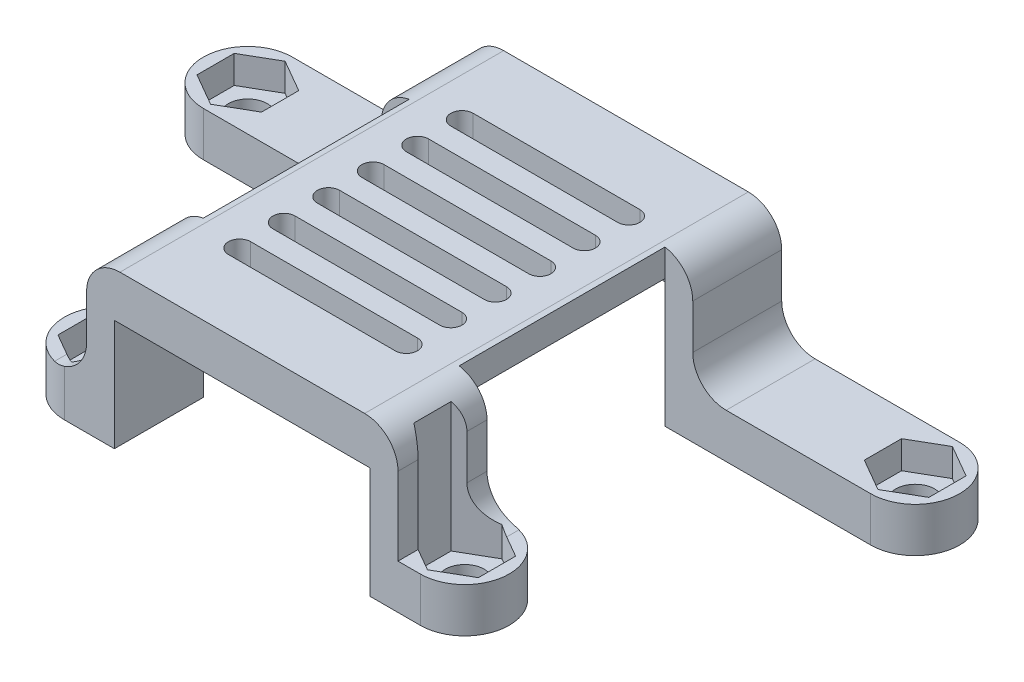
SolidWorks part; units mm, degrees
ref_plane "Front Plane" through (0, 0, 0) normal (0, 0, 1) x (1, 0, 0)
ref_plane "Top Plane" through (0, 0, 0) normal (0, 1, 0) x (1, 0, 0)
ref_plane "Right Plane" through (0, 0, 0) normal (1, 0, 0) x (0, 0, -1)
sketch "Sketch1" plane through (0, 0, 0) normal (0, 1, 0) x (1, 0, 0)
  line L0 (-7.6992, 0) -> (7.5789, 0) construction
  line L1 (0, 11.4586) -> (0, -5.7444) construction
  line L2 (0, 43.2) -> (0, -6.5) construction
  line L3 (-11.5, -6.5) -> (11.5, -6.5)
  line L4 (-11.5, -6.5) -> (-11.5, 43.2)
  line L5 (-11.5, 43.2) -> (11.5, 43.2)
  line L6 (11.5, -6.5) -> (11.5, 43.2)
  line L7 (-30, 30.5) -> (-11.5, 30.5)
  line L8 (-30, 22.5) -> (-11.5, 22.5)
  line L9 (-16, 4) -> (-11.5, 4)
  line L10 (-16, -4) -> (-11.5, -4)
  line L11 (16, -4) -> (11.5, -4)
  line L12 (16, 4) -> (11.5, 4)
  line L13 (30, 30.5) -> (11.5, 30.5)
  line L14 (30, 22.5) -> (11.5, 22.5)
  circle A0 centre (-16, 0) radius 1.75
  circle A1 centre (-30, 26.5) radius 1.75
  circle A2 centre (16, 0) radius 1.75
  circle A3 centre (16, 0) radius 4
  circle A4 centre (-30, 26.5) radius 4
  circle A5 centre (-16, 0) radius 4
  circle A6 centre (30, 26.5) radius 4
  circle A7 centre (30, 26.5) radius 1.75
  dimension "D2" = 3.5
  dimension "D8" = 8
  dimension "D1" = 32
  dimension "D3" = 60
  dimension "D4" = 26.5
  dimension "D5" = 23
  dimension "D6" = 49.7
  dimension "D7" = 6.5
extrude "Boss-Extrude1" add sketch "Sketch1" along normal blind 11.5 contours A4 A1 | A4 L8 L4 L7 | L14 A6 L13 L6 | A6 A7 | A3 A2 | L11 A3 L12 L6 | A5 L10 L4 L9 | A5 A0
sketch "Sketch2" plane through (0, 11.5, 0) normal (0, 1, 0) x (1, 0, 0)
  line L0 (-30, 22.5) -> (-11.5, 22.5) construction
  line L1 (-11.5, 30.5) -> (11.5, 30.5)
  line L2 (-11.5, 30.5) -> (-11.5, -4)
  line L3 (-11.5, -4) -> (11.5, -4)
  line L4 (11.5, 30.5) -> (11.5, -4)
  line L5 (-11.5, 22.5) -> (-11.5, 30.5) construction
  line L6 (-11.5, 30.5) -> (-30, 30.5) construction
  line L7 (-11.5, 4) -> (-16, 4) construction
  line L8 (-16, -4) -> (-11.5, -4) construction
  line L9 (-11.5, -4) -> (-11.5, 4) construction
  line L10 (11.5, 22.5) -> (30, 22.5) construction
  line L11 (30, 30.5) -> (11.5, 30.5) construction
  line L12 (11.5, 30.5) -> (11.5, 22.5) construction
  line L13 (16, 4) -> (11.5, 4) construction
  line L14 (11.5, 4) -> (11.5, -4) construction
  line L15 (11.5, -4) -> (16, -4) construction
  line L16 (-30, 22.5) -> (-11.5, 22.5)
  line L17 (-11.5, 22.5) -> (-11.5, 30.5)
  line L18 (-11.5, 30.5) -> (-30, 30.5)
  line L19 (-11.5, 4) -> (-16, 4)
  line L20 (-16, -4) -> (-11.5, -4)
  line L21 (-11.5, -4) -> (-11.5, 4)
  line L22 (11.5, 22.5) -> (30, 22.5)
  line L23 (30, 30.5) -> (11.5, 30.5)
  line L24 (11.5, 30.5) -> (11.5, 22.5)
  line L25 (16, 4) -> (11.5, 4)
  line L26 (11.5, 4) -> (11.5, -4)
  line L27 (11.5, -4) -> (16, -4)
  arc A0 (-30, 30.5) -> (-30, 22.5) centre (-30, 26.5) ccw construction
  arc A1 (-16, 4) -> (-16, -4) centre (-16, 0) ccw construction
  arc A2 (30, 22.5) -> (30, 30.5) centre (30, 26.5) ccw construction
  arc A3 (16, -4) -> (16, 4) centre (16, 0) ccw construction
  arc A4 (-30, 30.5) -> (-30, 22.5) centre (-30, 26.5) ccw
  arc A5 (-16, 4) -> (-16, -4) centre (-16, 0) ccw
  arc A6 (30, 22.5) -> (30, 30.5) centre (30, 26.5) ccw
  arc A7 (16, -4) -> (16, 4) centre (16, 0) ccw
  circle A8 centre (-30, 26.5) radius 1.75 construction
  circle A9 centre (-16, 0) radius 1.75 construction
  circle A10 centre (16, 0) radius 1.75 construction
  circle A11 centre (30, 26.5) radius 1.75 construction
  circle A12 centre (-30, 26.5) radius 1.75
  circle A13 centre (-16, 0) radius 1.75
  circle A14 centre (16, 0) radius 1.75
  circle A15 centre (30, 26.5) radius 1.75
  circle M1 centre (-30, 26.5) radius 1.75
  arc M2 (-30, 30.5) -> (-30, 22.5) centre (-30, 26.5) ccw
  line M3 (-30, 22.5) -> (-11.5, 22.5)
  line M4 (-11.5, 22.5) -> (-11.5, 30.5)
  line M5 (-11.5, 30.5) -> (-30, 30.5)
extrude "Boss-Extrude2" add sketch "Sketch2" along normal blind 2.5 contours M5 M2 M3 M4 M1 | L4 L1 L2 L3 M4 | L22 A6 L23 L4 A15 | L27 A7 L25 L4 A14 | L19 A5 L20 L2 A13
sketch "Sketch3" plane through (0, 14, 0) normal (0, 1, 0) x (1, 0, 0)
  line L0 (-14, 30.5) -> (-14, -4)
  line L1 (0, 30.5) -> (0, -4) construction
  line L2 (14, 30.5) -> (14, -4)
  line L8 (30, 30.5) -> (-30, 30.5)
  line L9 (-30, 22.5) -> (-11.5, 22.5)
  line L10 (-11.5, 22.5) -> (-11.5, 4)
  line L11 (-11.5, 4) -> (-16, 4)
  line L12 (-16, -4) -> (16, -4)
  line L13 (16, 4) -> (11.5, 4)
  line L14 (11.5, 4) -> (11.5, 22.5)
  line L15 (11.5, 22.5) -> (30, 22.5)
  line L16 (30, 30.5) -> (-30, 30.5)
  line L17 (-30, 22.5) -> (-11.5, 22.5)
  line L18 (-11.5, 22.5) -> (-11.5, 4)
  line L19 (-11.5, 4) -> (-16, 4)
  line L20 (-16, -4) -> (16, -4)
  line L21 (16, 4) -> (11.5, 4)
  line L22 (11.5, 4) -> (11.5, 22.5)
  line L23 (11.5, 22.5) -> (30, 22.5)
  circle A0 centre (-30, 26.5) radius 4
  arc A1 (-30, 30.5) -> (-30, 22.5) centre (-30, 26.5) ccw construction
  circle A2 centre (30, 26.5) radius 4
  arc A3 (30, 22.5) -> (30, 30.5) centre (30, 26.5) ccw construction
  circle A4 centre (-16, 0) radius 4
  arc A5 (-16, 4) -> (-16, -4) centre (-16, 0) ccw construction
  circle A6 centre (16, 0) radius 4
  arc A7 (16, -4) -> (16, 4) centre (16, 0) ccw construction
  arc A12 (-30, 30.5) -> (-30, 22.5) centre (-30, 26.5) ccw
  arc A13 (-16, 4) -> (-16, -4) centre (-16, 0) ccw
  arc A14 (16, -4) -> (16, 4) centre (16, 0) ccw
  arc A15 (30, 22.5) -> (30, 30.5) centre (30, 26.5) ccw
  arc A16 (-30, 30.5) -> (-30, 22.5) centre (-30, 26.5) ccw
  arc A17 (-16, 4) -> (-16, -4) centre (-16, 0) ccw
  arc A18 (16, -4) -> (16, 4) centre (16, 0) ccw
  arc A19 (30, 22.5) -> (30, 30.5) centre (30, 26.5) ccw
  line M13 (30, 30.5) -> (-30, 30.5)
  arc M14 (-30, 30.5) -> (-30, 22.5) centre (-30, 26.5) ccw
  line M15 (-30, 22.5) -> (-11.5, 22.5)
  line M17 (-11.5, 4) -> (-16, 4)
  arc M18 (-16, 4) -> (-16, -4) centre (-16, 0) ccw
  line M19 (-16, -4) -> (16, -4)
  arc M20 (16, -4) -> (16, 4) centre (16, 0) ccw
  line M21 (16, 4) -> (11.5, 4)
  line M23 (11.5, 22.5) -> (30, 22.5)
  arc M24 (30, 22.5) -> (30, 30.5) centre (30, 26.5) ccw
  circle M25 centre (-30, 26.5) radius 1.75
  circle M26 centre (-16, 0) radius 1.75
  circle M27 centre (16, 0) radius 1.75
  circle M28 centre (30, 26.5) radius 1.75
  dimension "D2" = 2.5
  dimension "D1" = 0
extrude "Cut-Extrude1" cut sketch "Sketch3" against normal offset from surface (10 mm away) 4 contours A0 M14 M25 | A0 L0 M15 M13 | A2 L2 M13 M23 | A2 M24 M28 | A6 L2 M20 M27 | A4 L0 M18 M26 | A4 L0 M19 | A4 L0 M17 | A6 L2 M21 | A6 L2 M19 up to face at (-14.75, 0, 0)
sketch "Sketch4" plane through (0, 14, 0) normal (0, 1, 0) x (1, 0, 0)
  line L0 (0, 30.5) -> (0, -4) construction
  line L1 (-27.1, 28.1743) -> (-30, 29.8486)
  line L2 (-30, 29.8486) -> (-32.9, 28.1743)
  line L3 (-32.9, 28.1743) -> (-32.9, 24.8257)
  line L4 (-32.9, 24.8257) -> (-30, 23.1514)
  line L5 (-30, 23.1514) -> (-27.1, 24.8257)
  line L6 (-27.1, 24.8257) -> (-27.1, 28.1743)
  line L7 (14, 30.5) -> (-14, 30.5) construction
  line L8 (-14, -4) -> (14, -4) construction
  line L9 (13.1, 1.6743) -> (16, 3.3486)
  line L10 (-13.1, 1.6743) -> (-16, 3.3486)
  line L11 (-16, 3.3486) -> (-18.9, 1.6743)
  line L12 (-18.9, 1.6743) -> (-18.9, -1.6743)
  line L13 (-18.9, -1.6743) -> (-16, -3.3486)
  line L14 (-16, -3.3486) -> (-13.1, -1.6743)
  line L15 (-13.1, -1.6743) -> (-13.1, 1.6743)
  line L16 (13.1, -1.6743) -> (13.1, 1.6743)
  line L17 (16, -3.3486) -> (13.1, -1.6743)
  line L18 (18.9, -1.6743) -> (16, -3.3486)
  line L19 (18.9, 1.6743) -> (18.9, -1.6743)
  line L20 (16, 3.3486) -> (18.9, 1.6743)
  line L21 (30, 23.1514) -> (27.1, 24.8257)
  line L22 (27.1, 24.8257) -> (27.1, 28.1743)
  line L23 (27.1, 28.1743) -> (30, 29.8486)
  line L24 (30, 29.8486) -> (32.9, 28.1743)
  line L25 (32.9, 28.1743) -> (32.9, 24.8257)
  line L26 (32.9, 24.8257) -> (30, 23.1514)
  circle A0 centre (-30, 26.5) radius 2.9 construction
  circle A1 centre (-16, 0) radius 2.9 construction
  dimension "D1" = 5.8
extrude "Cut-Extrude2" cut sketch "Sketch4" against normal offset from surface (12.5 mm away) 1.5 up to face at (-14.75, 0, 0)
sketch "Sketch5" plane through (0, 11.5, 0) normal (0, -1, 0) x (1, 0, 0)
  line L0 (-11.5, 4) -> (-11.5, -4) construction
  line L1 (-11.5, 0) -> (11.5, 0)
  line L2 (-11.5, 0) -> (-11.5, -23.75)
  line L3 (-11.5, -23.75) -> (11.5, -23.75)
  line L4 (11.5, 0) -> (11.5, -23.75)
  line L5 (11.5, -22.5) -> (11.5, -4) construction
  line L6 (-17.75, 0) -> (-14.25, 0) construction
  line L8 (-11.5, 4) -> (11.5, 4)
  line L9 (-11.5, 4) -> (-11.5, -30.5)
  line L10 (-11.5, -30.5) -> (11.5, -30.5)
  line L11 (11.5, 4) -> (11.5, -30.5)
  circle A0 centre (-16, 0) radius 1.75 construction
  line M1 (-11.5, 4) -> (-11.5, -4)
  line M3 (-11.5, -22.5) -> (-11.5, -30.5)
  line M4 (-11.5, -30.5) -> (11.5, -30.5)
  line M5 (11.5, -30.5) -> (11.5, -22.5)
  line M7 (11.5, -4) -> (11.5, 4)
  line M8 (11.5, 4) -> (-11.5, 4)
  dimension "D1" = 23.75
extrude "Boss-Extrude3" add sketch "Sketch5" along normal blind 1.5 contours L1 M1 M7 M8 | L3 M3 M4 M5
fillet "Fillet1" radius 3 7 edges at (14, 4, -26.5) (14, 14, -3.097) (14, 4, -3.097) (-14, 14, 3.097) (-14, 4, 3.097) (-14, 4, -3.097) (-14, 4, -26.5)
sketch "Sketch6" plane through (0, 14, 0) normal (0, 1, 0) x (1, 0, 0)
  line L0 (0, 30.5) -> (0, -4) construction
  line L1 (11, 30.5) -> (-11, 30.5) construction
  line L2 (-11, -4) -> (11, -4) construction
  line L3 (0, 13.25) -> (11.5, 13.25) construction
  line L4 (-7.5, 14.25) -> (-7.5, 12.25) construction
  line L5 (-7.5, 13.25) -> (7.5, 13.25) construction
  line L6 (-7.5, 23.25) -> (7.5, 23.25) construction
  line L7 (-7.5, 24.25) -> (7.5, 24.25)
  line L8 (-7.5, 22.25) -> (7.5, 22.25)
  line L9 (-7.5, 19.25) -> (7.5, 19.25) construction
  line L10 (-7.5, 20.25) -> (7.5, 20.25)
  line L11 (-7.5, 18.25) -> (7.5, 18.25)
  line L12 (-7.5, 15.25) -> (7.5, 15.25) construction
  line L13 (-7.5, 16.25) -> (7.5, 16.25)
  line L14 (-7.5, 14.25) -> (7.5, 14.25)
  line L15 (-7.5, 11.25) -> (7.5, 11.25) construction
  line L16 (-7.5, 12.25) -> (7.5, 12.25)
  line L17 (-7.5, 10.25) -> (7.5, 10.25)
  line L18 (-7.5, 7.25) -> (7.5, 7.25) construction
  line L19 (-7.5, 8.25) -> (7.5, 8.25)
  line L20 (-7.5, 6.25) -> (7.5, 6.25)
  line L21 (-7.5, 3.25) -> (7.5, 3.25) construction
  line L22 (-7.5, 4.25) -> (7.5, 4.25)
  line L23 (-7.5, 2.25) -> (7.5, 2.25)
  line L26 (7.5, 14.25) -> (7.5, 12.25) construction
  line L28 (11.5, 22.5) -> (11.5, 4) construction
  arc A0 (-7.5, 24.25) -> (-7.5, 22.25) centre (-7.5, 23.25) ccw
  arc A1 (7.5, 22.25) -> (7.5, 24.25) centre (7.5, 23.25) ccw
  arc A2 (-7.5, 20.25) -> (-7.5, 18.25) centre (-7.5, 19.25) ccw
  arc A3 (7.5, 18.25) -> (7.5, 20.25) centre (7.5, 19.25) ccw
  arc A4 (-7.5, 16.25) -> (-7.5, 14.25) centre (-7.5, 15.25) ccw
  arc A5 (7.5, 14.25) -> (7.5, 16.25) centre (7.5, 15.25) ccw
  arc A6 (-7.5, 12.25) -> (-7.5, 10.25) centre (-7.5, 11.25) ccw
  arc A7 (7.5, 10.25) -> (7.5, 12.25) centre (7.5, 11.25) ccw
  arc A8 (-7.5, 8.25) -> (-7.5, 6.25) centre (-7.5, 7.25) ccw
  arc A9 (7.5, 6.25) -> (7.5, 8.25) centre (7.5, 7.25) ccw
  arc A10 (-7.5, 4.25) -> (-7.5, 2.25) centre (-7.5, 3.25) ccw
  arc A11 (7.5, 2.25) -> (7.5, 4.25) centre (7.5, 3.25) ccw
  point P14 (0, 23.25)
  point P23 (0, 19.25)
  point P30 (0, 15.25)
  point P37 (0, 11.25)
  point P44 (0, 7.25)
  point P51 (0, 3.25)
  dimension "D1" = 15
  dimension "D2" = 2
  dimension "D3" = 4
  dimension "D4" = 6
extrude "Cut-Extrude3" cut sketch "Sketch6" against normal up to next
